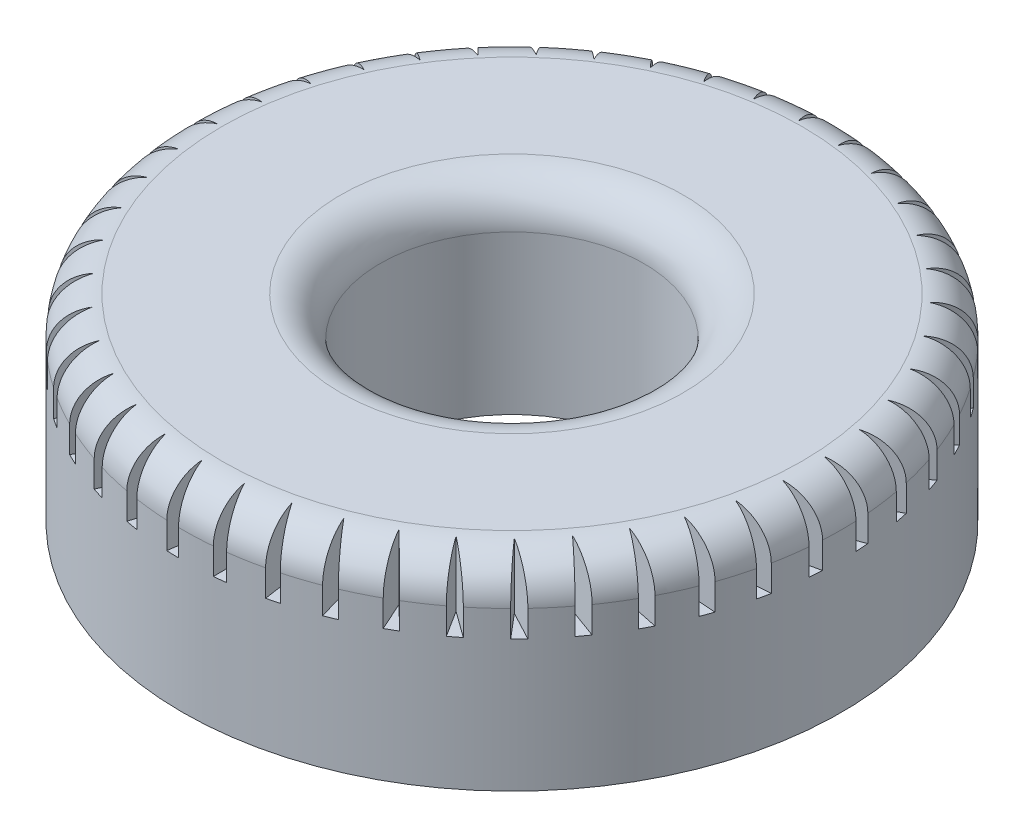
SolidWorks part; units mm, degrees
ref_plane "Front Plane" through (0, 0, 0) normal (0, 0, 1) x (1, 0, 0)
ref_plane "Top Plane" through (0, 0, 0) normal (0, 1, 0) x (1, 0, 0)
ref_plane "Right Plane" through (0, 0, 0) normal (1, 0, 0) x (0, 0, -1)
sketch "Sketch1" plane through (0, 0, 0) normal (0, 1, 0) x (1, 0, 0)
  circle A0 centre (-47.9036, 46.2903) radius 25
  circle A1 centre (-47.9036, 46.2903) radius 10
  dimension "D1" = 0
  dimension "D2" = 50
  dimension "D3" = 20
extrude "Boss-Extrude2" add sketch "Sketch1" along normal blind 15
fillet "Fillet3" radius 3 2 edges at (-47.9036, 15, -36.2903) (-47.9036, 15, -21.2903)
sketch "Sketch4" plane through (0, 15, 0) normal (0, 1, 0) x (1, 0, 0)
  line L0 (-49.4723, 71.7779) -> (-48.4198, 68.5453)
  line L1 (-48.2161, 71.7233) -> (-48.4198, 68.5453)
  line L2 (-49.4723, 71.7779) -> (-48.2161, 71.7233)
  line L3 (-45.8843, 71.7567) -> (-45.292, 68.4091)
  line L4 (-44.648, 71.5278) -> (-45.292, 68.4091)
  line L5 (-45.8843, 71.7567) -> (-44.648, 71.5278)
  line L6 (-42.3343, 71.2364) -> (-42.2136, 67.8389)
  line L7 (-41.1418, 70.8376) -> (-42.2136, 67.8389)
  line L8 (-42.3343, 71.2364) -> (-41.1418, 70.8376)
  line L9 (-38.8912, 70.2271) -> (-39.2445, 66.8458)
  line L10 (-37.7658, 69.6662) -> (-39.2445, 66.8458)
  line L11 (-38.8912, 70.2271) -> (-37.7658, 69.6662)
  line L12 (-35.6221, 68.7484) -> (-36.4425, 65.4492)
  line L13 (-34.5857, 68.0364) -> (-36.4425, 65.4492)
  line L14 (-35.6221, 68.7484) -> (-34.5857, 68.0364)
  line L15 (-32.5906, 66.8291) -> (-33.8622, 63.6762)
  line L16 (-31.6634, 65.9798) -> (-33.8622, 63.6762)
  line L17 (-32.5906, 66.8291) -> (-31.6634, 65.9798)
  line L18 (-29.8557, 64.5066) -> (-31.5537, 61.5614)
  line L19 (-29.0557, 63.5365) -> (-31.5537, 61.5614)
  line L20 (-29.8557, 64.5066) -> (-29.0557, 63.5365)
  line L21 (-27.4706, 61.8261) -> (-29.562, 59.1458)
  line L22 (-26.8134, 60.7541) -> (-29.562, 59.1458)
  line L23 (-27.4706, 61.8261) -> (-26.8134, 60.7541)
  line L24 (-25.4818, 58.8397) -> (-27.9259, 56.4766)
  line L25 (-24.9802, 57.6867) -> (-27.9259, 56.4766)
  line L26 (-25.4818, 58.8397) -> (-24.9802, 57.6867)
  line L27 (-23.928, 55.6056) -> (-26.6772, 53.6057)
  line L28 (-23.5918, 54.394) -> (-26.6772, 53.6057)
  line L29 (-23.928, 55.6056) -> (-23.5918, 54.394)
  line L30 (-22.8394, 52.1867) -> (-25.8402, 50.5889)
  line L31 (-22.6751, 50.9401) -> (-25.8402, 50.5889)
  line L32 (-22.8394, 52.1867) -> (-22.6751, 50.9401)
  line L33 (-22.2373, 48.6496) -> (-25.4312, 47.4849)
  line L34 (-22.248, 47.3923) -> (-25.4312, 47.4849)
  line L35 (-22.2373, 48.6496) -> (-22.248, 47.3923)
  line L36 (-22.1332, 45.0631) -> (-25.4582, 44.3543)
  line L37 (-22.3189, 43.8195) -> (-25.4582, 44.3543)
  line L38 (-22.1332, 45.0631) -> (-22.3189, 43.8195)
  line L39 (-22.5293, 41.4971) -> (-25.9206, 41.2579)
  line L40 (-22.8862, 40.2914) -> (-25.9206, 41.2579)
  line L41 (-22.5293, 41.4971) -> (-22.8862, 40.2914)
  line L42 (-23.4179, 38.0208) -> (-26.8094, 38.256)
  line L43 (-23.9391, 36.8766) -> (-26.8094, 38.256)
  line L44 (-23.4179, 38.0208) -> (-23.9391, 36.8766)
  line L45 (-24.7816, 34.7021) -> (-28.1074, 35.4069)
  line L46 (-25.457, 33.6415) -> (-28.1074, 35.4069)
  line L47 (-24.7816, 34.7021) -> (-25.457, 33.6415)
  line L48 (-26.5939, 31.6055) -> (-29.7892, 32.7663)
  line L49 (-27.4103, 30.6492) -> (-29.7892, 32.7663)
  line L50 (-26.5939, 31.6055) -> (-27.4103, 30.6492)
  line L51 (-28.8196, 28.7912) -> (-31.8222, 30.3854)
  line L52 (-29.7611, 27.9578) -> (-31.8222, 30.3854)
  line L53 (-28.8196, 28.7912) -> (-29.7611, 27.9578)
  line L54 (-31.4152, 26.314) -> (-34.1668, 28.3106)
  line L55 (-32.4636, 25.6198) -> (-34.1668, 28.3106)
  line L56 (-31.4152, 26.314) -> (-32.4636, 25.6198)
  line L57 (-34.3304, 24.2222) -> (-36.7773, 26.5824)
  line L58 (-35.4652, 23.6807) -> (-36.7773, 26.5824)
  line L59 (-34.3304, 24.2222) -> (-35.4652, 23.6807)
  line L60 (-37.5083, 22.5565) -> (-39.6029, 25.2342)
  line L61 (-38.7074, 22.1782) -> (-39.6029, 25.2342)
  line L62 (-37.5083, 22.5565) -> (-38.7074, 22.1782)
  line L63 (-40.8871, 21.3493) -> (-42.5886, 24.2924)
  line L64 (-42.1272, 21.1415) -> (-42.5886, 24.2924)
  line L65 (-40.8871, 21.3493) -> (-42.1272, 21.1415)
  line L66 (-44.401, 20.624) -> (-45.6764, 23.7754)
  line L67 (-45.6579, 20.5909) -> (-45.6764, 23.7754)
  line L68 (-44.401, 20.624) -> (-45.6579, 20.5909)
  line L69 (-47.9817, 20.3949) -> (-48.8061, 23.693)
  line L70 (-49.231, 20.537) -> (-48.8061, 23.693)
  line L71 (-47.9817, 20.3949) -> (-49.231, 20.537)
  line L72 (-51.5594, 20.6663) -> (-51.9168, 24.0471)
  line L73 (-52.7768, 20.9809) -> (-51.9168, 24.0471)
  line L74 (-51.5594, 20.6663) -> (-52.7768, 20.9809)
  line L75 (-55.0645, 21.433) -> (-54.9479, 24.8306)
  line L76 (-56.2263, 21.914) -> (-54.9479, 24.8306)
  line L77 (-55.0645, 21.433) -> (-56.2263, 21.914)
  line L78 (-58.4288, 22.68) -> (-57.8405, 26.0284)
  line L79 (-59.5123, 23.318) -> (-57.8405, 26.0284)
  line L80 (-58.4288, 22.68) -> (-59.5123, 23.318)
  line L81 (-61.5868, 24.3832) -> (-60.5382, 27.6171)
  line L82 (-62.571, 25.1657) -> (-60.5382, 27.6171)
  line L83 (-61.5868, 24.3832) -> (-62.571, 25.1657)
  line L84 (-64.4771, 26.5093) -> (-62.9886, 29.5657)
  line L85 (-65.3427, 27.4212) -> (-62.9886, 29.5657)
  line L86 (-64.4771, 26.5093) -> (-65.3427, 27.4212)
  line L87 (-67.0433, 29.0169) -> (-65.1439, 31.8365)
  line L88 (-67.7736, 30.0404) -> (-65.1439, 31.8365)
  line L89 (-67.0433, 29.0169) -> (-67.7736, 30.0404)
  line L90 (-69.2355, 31.8572) -> (-66.9622, 34.385)
  line L91 (-69.8163, 32.9725) -> (-66.9622, 34.385)
  line L92 (-69.2355, 31.8572) -> (-69.8163, 32.9725)
  line L93 (-71.0111, 34.9751) -> (-68.4082, 37.1619)
  line L94 (-71.4311, 36.1603) -> (-68.4082, 37.1619)
  line L95 (-71.0111, 34.9751) -> (-71.4311, 36.1603)
  line L96 (-72.3356, 38.3097) -> (-69.4536, 40.113)
  line L97 (-72.5865, 39.5418) -> (-69.4536, 40.113)
  line L98 (-72.3356, 38.3097) -> (-72.5865, 39.5418)
  line L99 (-73.183, 41.7962) -> (-70.0781, 43.1808)
  line L100 (-73.26, 43.0512) -> (-70.0781, 43.1808)
  line L101 (-73.183, 41.7962) -> (-73.26, 43.0512)
  line L102 (-73.537, 45.3667) -> (-70.2696, 46.3057)
  line L103 (-73.4386, 46.6202) -> (-70.2696, 46.3057)
  line L104 (-73.537, 45.3667) -> (-73.4386, 46.6202)
  line L105 (-73.3906, 48.9517) -> (-70.0243, 49.4268)
  line L106 (-73.1187, 50.1793) -> (-70.0243, 49.4268)
  line L107 (-73.3906, 48.9517) -> (-73.1187, 50.1793)
  line L108 (-72.7467, 52.4814) -> (-69.347, 52.4834)
  line L109 (-72.3066, 53.6592) -> (-69.347, 52.4834)
  line L110 (-72.7467, 52.4814) -> (-72.3066, 53.6592)
  line L111 (-71.6178, 55.8872) -> (-68.251, 55.4161)
  line L112 (-71.018, 56.9923) -> (-68.251, 55.4161)
  line L113 (-71.6178, 55.8872) -> (-71.018, 56.9923)
  line L114 (-70.0259, 59.1027) -> (-66.7574, 58.1676)
  line L115 (-69.2782, 60.1136) -> (-66.7574, 58.1676)
  line L116 (-70.0259, 59.1027) -> (-69.2782, 60.1136)
  line L117 (-68.002, 62.0654) -> (-64.8954, 60.6845)
  line L118 (-67.1209, 62.9624) -> (-64.8954, 60.6845)
  line L119 (-68.002, 62.0654) -> (-67.1209, 62.9624)
  line L120 (-65.5855, 64.7176) -> (-62.7013, 62.9177)
  line L121 (-64.5881, 65.4832) -> (-62.7013, 62.9177)
  line L122 (-65.5855, 64.7176) -> (-64.5881, 65.4832)
  line L123 (-62.8233, 67.0076) -> (-60.2177, 64.8239)
  line L124 (-61.7291, 67.627) -> (-60.2177, 64.8239)
  line L125 (-62.8233, 67.0076) -> (-61.7291, 67.627)
  line L126 (-59.7694, 68.891) -> (-57.4931, 66.3659)
  line L127 (-58.5996, 69.352) -> (-57.4931, 66.3659)
  line L128 (-59.7694, 68.891) -> (-58.5996, 69.352)
  line L129 (-56.483, 70.3309) -> (-54.5803, 67.5136)
  line L130 (-55.2604, 70.6247) -> (-54.5803, 67.5136)
  line L131 (-56.483, 70.3309) -> (-55.2604, 70.6247)
  line L132 (-53.0282, 71.2995) -> (-51.5361, 68.2449)
  line L133 (-51.7767, 71.4203) -> (-51.5361, 68.2449)
  line L134 (-53.0282, 71.2995) -> (-51.7767, 71.4203)
  point P138 (-47.8298, 46.1124)
  dimension "D1" = 45
extrude "Cut-Extrude3" cut sketch "Sketch4" against normal blind 5
